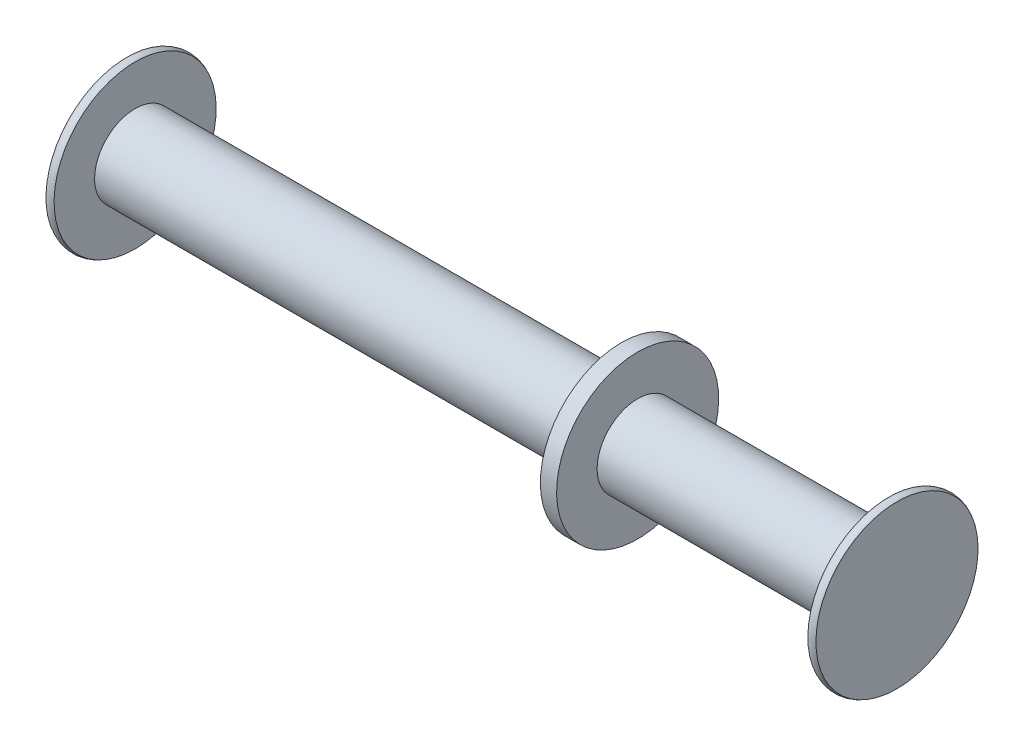
SolidWorks part; units mm, degrees
ref_plane "Ön Düzlem" through (0, 0, 0) normal (0, 0, 1) x (1, 0, 0)
ref_plane "Üst Düzlem" through (0, 0, 0) normal (0, 1, 0) x (1, 0, 0)
ref_plane "Sağ Düzlem" through (0, 0, 0) normal (1, 0, 0) x (0, 0, -1)
sketch "Sketch1" plane through (0, 0, 0) normal (0, 0, 1) x (1, 0, 0)
  line L0 (-47.5, 0) -> (47.5, 0)
  line L1 (-47.5, 0) -> (-47.5, -10)
  line L2 (-42.5, -5) -> (12.75, -5) construction
  line L3 (-46.5, -5) -> (46.5, -5)
  line L4 (-42.5, -5) -> (-42.5, -10) construction
  line L5 (-46.5, -1) -> (-46.5, -10) construction
  line L6 (-46.5, -5) -> (-46.5, -10)
  line L7 (-46.5, -1) -> (12.75, -1) construction
  line L8 (0, 0) -> (0, -5.3304) construction
  line L9 (-47.5, 0) -> (12.75, 0) construction
  line L10 (46.5, -5) -> (46.5, -10)
  line L11 (47.5, 0) -> (47.5, -10)
  arc A0 (-47.5, -10) -> (-46.5, -10) centre (-47, -9.134) ccw
  arc A1 (47.5, -10) -> (46.5, -10) centre (47, -9.134) cw
  point P20 (0, -5)
  dimension "D1" = 47.5
  dimension "D2" = 10
  dimension "D3" = 5
  dimension "D4" = 1
revolve "Revolve1" add sketch "Sketch1" angle 360 about L0
ref_plane "Plane1" through (13.5, 0, 0) normal (1, 0, 0) x (0, 0, -1)
sketch "Sketch2" plane through (13.5, 0, 0) normal (1, 0, 0) x (0, 0, -1)
  circle A0 centre (0, 0) radius 10
extrude "Boss-Extrude1" add sketch "Sketch2" along normal blind 2
